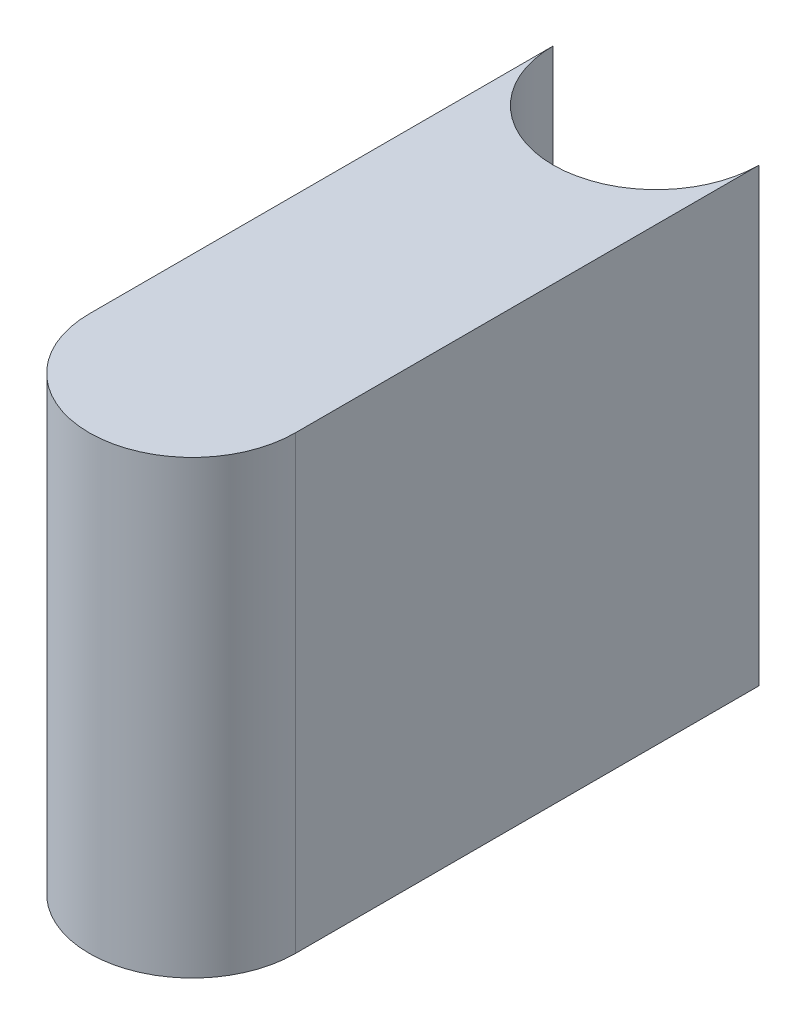
SolidWorks part; units mm, degrees
ref_plane "Front Plane" through (0, 0, 0) normal (0, 0, 1) x (1, 0, 0)
ref_plane "Top Plane" through (0, 0, 0) normal (0, 1, 0) x (1, 0, 0)
ref_plane "Right Plane" through (0, 0, 0) normal (1, 0, 0) x (0, 0, -1)
sketch "Sketch1" plane through (0, 0, 0) normal (0, 1, 0) x (1, 0, 0)
  line L2 (-90.3414, 354.1111) -> (-90.3414, -5.8889)
  line L4 (69.6586, 354.1111) -> (69.6586, -5.8889)
  arc A0 (-90.3414, -5.8889) -> (69.6586, -5.8889) centre (-10.3414, -5.8889) ccw
  arc A2 (-90.3414, 354.1111) -> (69.6586, 354.1111) centre (-10.3414, 354.1111) ccw
  point P3 (1049.3878, 516.5143)
  point P4 (1088.6894, 477.2127)
  dimension "D1" = 160
  dimension "D2" = 80
  dimension "D6" = 80
  dimension "D3" = 360
  dimension "D4" = 160
  dimension "D5" = 360
extrude "Boss-Extrude1" add sketch "Sketch1" along normal blind 350
